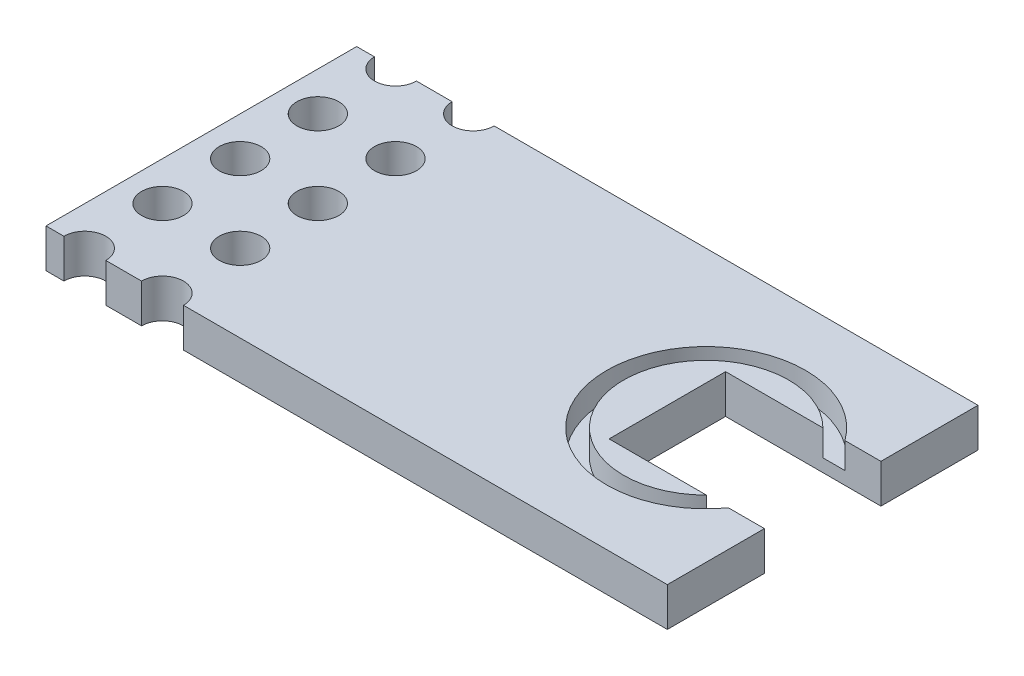
SolidWorks part; units mm, degrees
ref_plane "Front Plane" through (0, 0, 0) normal (0, 0, 1) x (1, 0, 0)
ref_plane "Top Plane" through (0, 0, 0) normal (0, 1, 0) x (1, 0, 0)
ref_plane "Right Plane" through (0, 0, 0) normal (1, 0, 0) x (0, 0, -1)
sketch "Sketch1" plane through (0, 0, 0) normal (0, 1, 0) x (1, 0, 0)
  line L1 (-76.2, -44.45) -> (76.2, -44.45)
  line L2 (-76.2, -44.45) -> (-76.2, 44.45)
  line L3 (-76.2, 44.45) -> (76.2, 44.45)
  line L4 (76.2, -44.45) -> (76.2, 44.45)
  line L5 (-76.2, -44.45) -> (76.2, 44.45) construction
  line L6 (-76.2, 44.45) -> (76.2, -44.45) construction
  circle A0 centre (-69.85, 38.1) radius 3.429
  circle A2 centre (-57.15, 38.1) radius 3.429
  circle A3 centre (-57.15, 25.4) radius 3.429
  circle A4 centre (-57.15, 12.7) radius 3.429
  circle A5 centre (-57.15, 0) radius 3.429
  circle A6 centre (-57.15, -12.7) radius 3.429
  circle A7 centre (-57.15, -25.4) radius 3.429
  circle A8 centre (-57.15, -38.1) radius 3.429
  circle A10 centre (-69.85, 25.4) radius 3.429
  circle A11 centre (-69.85, 12.7) radius 3.429
  circle A12 centre (-69.85, 0) radius 3.429
  circle A13 centre (-69.85, -12.7) radius 3.429
  circle A14 centre (-69.85, -25.4) radius 3.429
  circle A15 centre (-69.85, -38.1) radius 3.429
  point P0 (0, 0)
  dimension "D3" = 6.858
  dimension "D5" = 6.35
  dimension "D4" = 6.35
  dimension "D1" = 88.9
  dimension "D2" = 152.4
  dimension "D6" = 2
  dimension "D7" = 7
extrude "Boss-Extrude1" add sketch "Sketch1" along normal blind 6.35
sketch "Sketch2" plane through (0, 0, 0) normal (0, 1, 0) x (1, 0, 0)
  circle A0 centre (6.35, 0) radius 13.5
  circle A1 centre (6.35, 0) radius 16.25
  dimension "D1" = 27
  dimension "D2" = 32.5
  dimension "D3" = 6.35
extrude "Cut-Extrude3" cut sketch "Sketch2" against normal blind 4.25 from surface at 6.35 contours A0 | A1 starting at face at (0, 6.35, 0)
sketch "Sketch3" plane through (0, 6.35, 0) normal (0, 1, 0) x (1, 0, 0)
  line L0 (76.2, -44.45) -> (76.2, 44.45) construction
  line L1 (0, 9.525) -> (76.2, 9.525)
  line L2 (0, 9.525) -> (0, -9.525)
  line L3 (0, -9.525) -> (76.2, -9.525)
  line L4 (76.2, 9.525) -> (76.2, -9.525)
  point P6 (0, 0)
  dimension "D2" = 19.05
extrude "Cut-Extrude4" cut sketch "Sketch3" against normal through all
sketch "Sketch4" plane through (0, 0, 0) normal (0, 1, 0) x (1, 0, 0)
  line L0 (-76.2, -44.45) -> (-76.2, -25.4) construction
  line L1 (-76.2, -44.45) -> (76.2, -44.45) construction
  line L2 (-76.2, -25.4) -> (25.4, -25.4)
  line L3 (25.4, -25.4) -> (25.4, 25.4)
  line L4 (25.4, 25.4) -> (-76.2, 25.4)
  line L5 (-76.2, 25.4) -> (-76.2, 44.45) construction
  line L6 (76.2, 44.45) -> (-76.2, 44.45) construction
  line L7 (-76.2, 44.45) -> (-76.2, -44.45) construction
  line L8 (-76.2, 25.4) -> (-76.2, -25.4)
  dimension "D1" = 50.8
  dimension "D2" = 101.6
extrude "Cut-Extrude6" cut sketch "Sketch4" along normal through all flip side to cut
